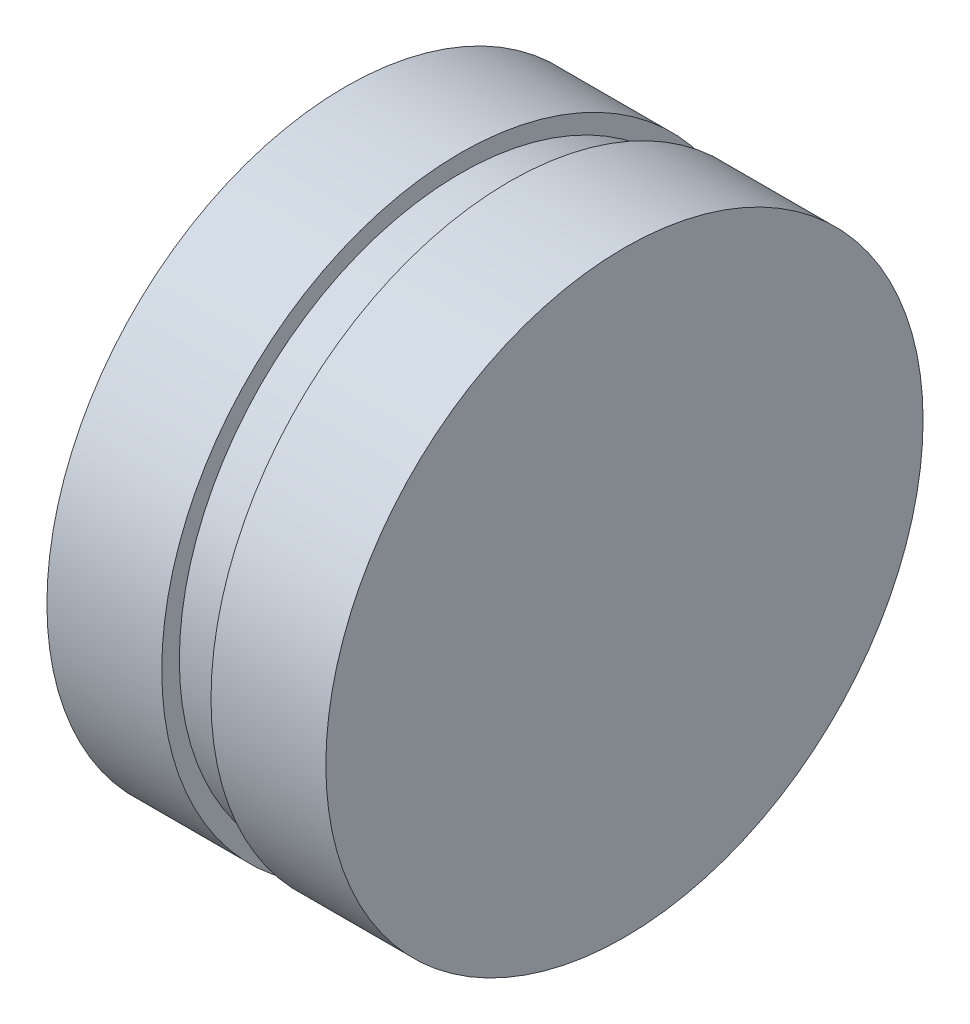
SolidWorks part; units mm, degrees
material "6061-T6 (SS)"
ref_plane "Front Plane" through (0, 0, 0) normal (0, 0, 1) x (1, 0, 0)
ref_plane "Top Plane" through (0, 0, 0) normal (0, 1, 0) x (1, 0, 0)
ref_plane "Right Plane" through (0, 0, 0) normal (1, 0, 0) x (0, 0, -1)
ref_axis "Axis1" through (-14.407, 0, 0) along (1, 0, 0)
sketch "Sketch1" [suppressed] plane through (0, 0, 0) normal (0, 0, 1) x (1, 0, 0)
  line L0 (0, -55) -> (0, 55) construction
  line L1 (0, 34.8234) -> (101.6, 34.8234)
  line L2 (0, 34.8234) -> (0, 0)
  line L3 (0, 0) -> (101.6, 0)
  line L4 (101.6, 34.8234) -> (101.6, 0)
  line L5 (55, 0) -> (-55, 0) construction
  dimension "D1" = 34.8234
  dimension "D2" = 101.6
revolve "Revolve1" [suppressed] add sketch "Sketch1" angle 360 about axis through (-14.407, 0, 0) along (1, 0, 0)
sketch "Sketch2" [suppressed] plane through (0, 0, 0) normal (0, 0, 1) x (1, 0, 0)
  line L0 (0, 28.4734) -> (10.16, 28.4734)
  line L1 (0, -55) -> (0, 55) construction
  line L2 (0, 28.4734) -> (0, 0)
  line L3 (101.6, 24.9936) -> (101.6, 0)
  line L5 (101.6, -34.8234) -> (101.6, 34.8234) construction
  line L7 (101.6, 0) -> (0, 0)
  line L8 (48.1206, 8.8004) -> (59.2205, 13.9763) construction
  line L9 (101.6, 24.9936) -> (122.8287, 29.12) construction
  arc A0 (10.16, 28.4734) -> (36.83, 14.151) centre (10.16, -3.5192) cw
  arc A1 (36.83, 14.151) -> (46.482, 8.5) centre (47.4171, 21.1655) ccw
  arc A2 (46.482, 8.5) -> (48.1206, 8.8004) centre (46.7251, 11.793) ccw
  parabola Q0 (101.6, 24.9936) -> (48.1206, 8.8004) focus (30.6468, -36.2749) apex (8.7156, -28.8042)
  dimension "D3" = 3.302
  dimension "D4" = 12.7
  dimension "D1" = 28.4734
  dimension "D2" = 10.16
  dimension "D5" = 25
  dimension "D6" = 26.67
  dimension "D7" = 8.5
  dimension "D8" = 11
  dimension "D9" = 46.482
  dimension "D10" = 24.9936
revolve "Cut-Revolve1" [suppressed] cut sketch "Sketch2" angle 360 about axis through (-14.407, 0, 0) along (1, 0, 0)
sketch "Sketch3" [suppressed] plane through (0, 0, 0) normal (0, 0, 1) x (1, 0, 0)
  line L0 (0, -55) -> (0, 55) construction
  line L1 (0, 34.8234) -> (6.35, 34.8234)
  line L2 (0, 34.8234) -> (0, 32.1564)
  line L3 (0, 32.1564) -> (6.35, 32.1564)
  line L4 (6.35, 34.8234) -> (6.35, 32.1564)
  line L5 (-14.407, 0) -> (111.4249, 0) construction
  dimension "D1" = 6.35
  dimension "D2" = 32.1564
  dimension "D3" = 34.8234
revolve "Cut-Revolve2" [suppressed] cut sketch "Sketch3" angle 360 about axis through (-14.407, 0, 0) along (1, 0, 0)
sketch "Sketch4" [suppressed] plane through (0, 0, 0) normal (0, 0, 1) x (1, 0, 0)
  line L0 (101.6, -34.8234) -> (101.6, 34.8234) construction
  line L1 (101.6, 25.8064) -> (63.5, 25.8064)
  line L2 (101.6, 25.8064) -> (101.6, 34.8234)
  line L3 (101.6, 34.8234) -> (63.5, 34.8234)
  line L4 (63.5, 25.8064) -> (63.5, 34.8234)
  line L5 (-14.407, 0) -> (111.4249, 0) construction
  dimension "D1" = 9.017
  dimension "D2" = 38.1
  dimension "D3" = 34.8234
revolve "Cut-Revolve3" [suppressed] cut sketch "Sketch4" angle 360 about axis through (-14.407, 0, 0) along (1, 0, 0)
sketch "Sketch5" [suppressed] plane through (0, 0, 0) normal (0, 0, 1) x (1, 0, 0)
  line L0 (36.83, 0) -> (36.83, 21.59)
  line L1 (38.3057, 0) -> (-38.3057, 0) construction
  line L2 (36.83, 21.59) -> (57.15, 21.59)
  line L3 (57.15, 21.59) -> (57.15, 0)
  line L4 (57.15, 0) -> (101.6, 0)
  line L5 (101.6, -24.9936) -> (101.6, 24.9936) construction
  line L6 (101.6, 0) -> (101.6, 34.8234)
  line L7 (101.6, 34.8234) -> (0, 34.8234)
  line L8 (0, -38.3057) -> (0, 38.3057) construction
  line L9 (0, 34.8234) -> (0, 0)
  line L10 (0, 0) -> (36.83, 0)
  line L11 (-14.407, 0) -> (111.4249, 0) construction
  dimension "D1" = 34.8234
  dimension "D2" = 21.59
  dimension "D3" = 36.83
  dimension "D4" = 20.32
revolve "Cut-Revolve4" [suppressed] cut sketch "Sketch5" angle 360 about axis through (-14.407, 0, 0) along (1, 0, 0)
ref_plane "Offset Plane (same position as insert)" through (36.83, 0, 0) normal (1, 0, 0) x (0, 0, -1)
sketch "Sketch8" plane through (36.83, 0, 0) normal (1, 0, 0) x (0, 0, -1)
  circle A0 centre (0, 0) radius 21.5646
  dimension "D1" = 43.1292
extrude "Boss-Extrude1" add sketch "Sketch8" along normal blind 20.1422
sketch "Sketch9" plane through (0, 0, 0) normal (0, 0, 1) x (1, 0, 0)
  line L0 (56.9722, 21.5646) -> (36.83, 21.5646) construction
  line L1 (45.1231, 21.5646) -> (48.6791, 21.5646)
  line L2 (45.1231, 21.5646) -> (45.1231, 20.2946)
  line L3 (45.1231, 20.2946) -> (48.6791, 20.2946)
  line L4 (48.6791, 21.5646) -> (48.6791, 20.2946)
  line L6 (56.9722, 21.5646) -> (36.83, 21.5646) construction
  point P7 (46.9011, 21.5646)
  point P8 (46.9011, 21.5646)
  dimension "D1" = 3.556
  dimension "D2" = 1.27
revolve "O-Ring Groove 2-128ish" cut sketch "Sketch9" angle 360 about axis through (-14.407, 0, 0) along (1, 0, 0)
equation "\"throat_radius\"= 8.5mm"
equation "\"diverg_circle_rad\"= 0.382 * \"throat_radius\""
equation "\"converg_circle_rad\"= 1.5 * \"throat_radius\""
